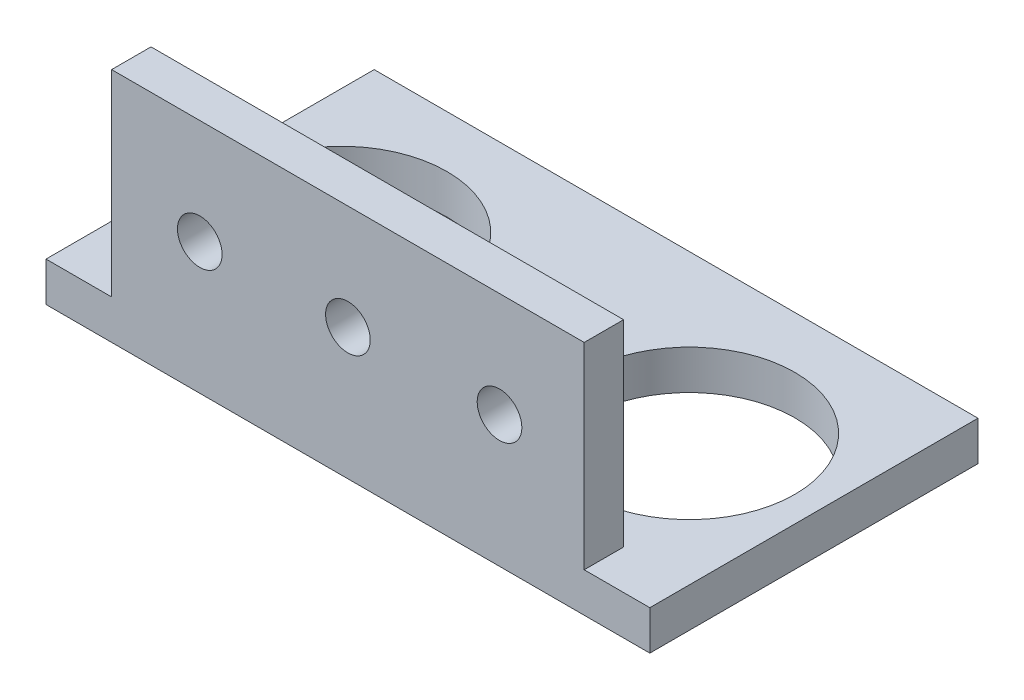
SolidWorks part; units mm, degrees
ref_plane "Front Plane" through (0, 0, 0) normal (0, 0, 1) x (1, 0, 0)
ref_plane "Top Plane" through (0, 0, 0) normal (0, 1, 0) x (1, 0, 0)
ref_plane "Right Plane" through (0, 0, 0) normal (1, 0, 0) x (0, 0, -1)
sketch "Skizze1" plane through (0, 0, 0) normal (0, 1, 0) x (1, 0, 0)
  line L1 (-23, -12.5) -> (23, -12.5)
  line L2 (-23, -12.5) -> (-23, 12.5)
  line L3 (-23, 12.5) -> (23, 12.5)
  line L4 (23, -12.5) -> (23, 12.5)
  line L5 (-23, -12.5) -> (23, 12.5) construction
  line L6 (-23, 12.5) -> (23, -12.5) construction
  point P0 (0, 0)
  dimension "D1" = 46
  dimension "D2" = 25
extrude "Aufsatz-Linear austragen1" add sketch "Skizze1" along normal blind 3
sketch "Skizze3" plane through (0, 3, 0) normal (0, 1, 0) x (1, 0, 0)
  line L0 (23, -12.5) -> (23, 12.5) construction
  line L1 (-23, -12.5) -> (23, -12.5)
  line L2 (-23, -12.5) -> (-23, -9.5)
  line L3 (-23, -9.5) -> (23, -9.5)
  line L4 (23, -12.5) -> (23, -9.5)
  dimension "D1" = 3
extrude "Aufsatz-Linear austragen2" add sketch "Skizze3" along normal blind 15
sketch "Skizze6" plane through (0, 0, 9.5) normal (0, 0, -1) x (-1, 0, 0)
  point P0 (-17.2338, 10.7496)
  point P2 (0, 10.7496)
  point P4 (15.0468, 10.7496)
sketch "Skizze7" plane through (0, 0, 9.5) normal (0, 0, -1) x (-1, 0, 0)
  line L0 (-23, 3) -> (23, 3) construction
  line L1 (-23, 18) -> (23, 18) construction
  line L2 (0, 18) -> (0, 3) construction
  line L4 (-23, 18) -> (-18, 18)
  line L5 (-23, 18) -> (-23, 3)
  line L6 (-23, 3) -> (-18, 3)
  line L7 (-18, 18) -> (-18, 3)
  line L8 (18, 18) -> (23, 18)
  line L9 (18, 18) -> (18, 3)
  line L10 (18, 3) -> (23, 3)
  line L11 (23, 18) -> (23, 3)
  dimension "D1" = 5
extrude "Schnitt-Linear austragen1" cut sketch "Skizze7" against normal up to next contours L5 L4 L7 L6 | L9 L8 L11 L10
sketch "Skizze10" plane through (0, 0, 9.5) normal (0, 0, -1) x (-1, 0, 0)
  point P0 (-11.5475, 10.006)
  point P2 (0, 10.006)
  point P4 (11.2851, 10.006)
hole_wizard "Ø3.4 (3.4) Diameter Hole2" positions "Skizze10" profile "Skizze9" hole size "Ø3.4" standard "ANSI Metric" end condition through all
sketch "Skizze9" plane through (11.5475, 10.006, 9.5) normal (1, 0, 0) x (0, 1, 0)
  line L0 (0, 0) -> (0, 3)
  line L1 (0, 3) -> (1.7, 3)
  line L2 (1.7, 3) -> (1.7, 0.025)
  line L3 (1.7, 0.025) -> (1.725, 0)
  line L5 (1.725, 0) -> (0, 0)
  line L6 (-1.7, 0.025) -> (-1.725, 0) construction
  line L11 (0, -6.35) -> (0, 107.95) construction
  dimension "Thru Hole Dia." = 3.4
  dimension "Thru Hole Depth" = 3
  dimension "Near C'Sink Dia." = 3.45
  dimension "Near C'Sink Angle" = 90
sketch "Skizze12" plane through (0, 0, 0) normal (0, -1, 0) x (1, 0, 0)
  line L1 (23, 12.5) -> (23, -12.5) construction
  line L2 (23, -12.5) -> (-23, -12.5) construction
  line L3 (-23, 12.5) -> (23, 12.5) construction
  line L4 (-6.5, 9.3) -> (5.5, 9.3)
  line L5 (-6.5, 9.3) -> (-6.5, 5.3)
  line L6 (-6.5, 5.3) -> (5.5, 5.3)
  line L7 (5.5, 9.3) -> (5.5, 5.3)
  circle A0 centre (-13.5, -0.5) radius 8.05
  circle A1 centre (13, -0.5) radius 8.05
  dimension "D2" = 16.1
  dimension "D3" = 10
  dimension "D4" = 12
  dimension "D1" = 26.5
  dimension "D5" = 4
  dimension "D6" = 12
  dimension "D7" = 3.2
  dimension "D8" = 17.5
extrude "Schnitt-Linear austragen2" cut sketch "Skizze12" against normal up to next contours A0 | A1 | L6 L7 L4 L5
